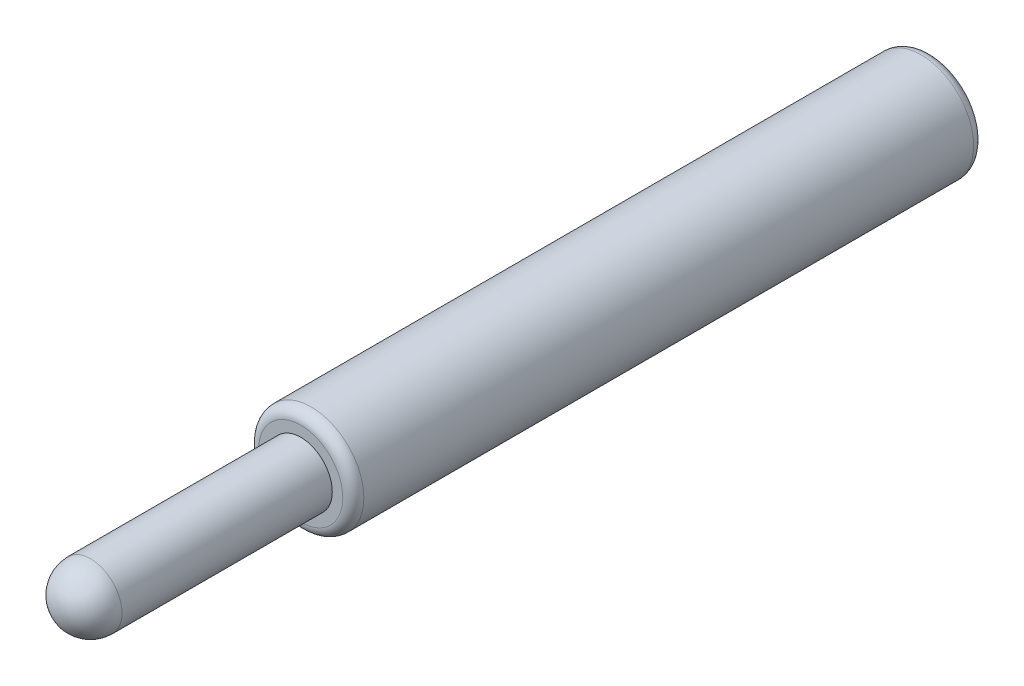
SolidWorks part; units mm, degrees
ref_plane "前视基准面" through (0, 0, 0) normal (0, 0, 1) x (1, 0, 0)
ref_plane "上视基准面" through (0, 0, 0) normal (0, 1, 0) x (1, 0, 0)
ref_plane "右视基准面" through (0, 0, 0) normal (1, 0, 0) x (0, 0, -1)
sketch "草图1" plane through (0, 0, 0) normal (0, 0, 1) x (1, 0, 0)
  circle A0 centre (0, 0) radius 5
  dimension "D1" = 10
extrude "凸台-拉伸1" add sketch "草图1" against normal blind 60
sketch "草图2" plane through (0, 0, 0) normal (0, 0, 1) x (1, 0, 0)
  circle A0 centre (0, 0) radius 3
  dimension "D1" = 6
extrude "凸台-拉伸2" add sketch "草图2" along normal blind 20
fillet "圆角1" radius 1 2 edges at (5, 0, -60) (5, 0, 0)
sketch "草图3" plane through (0, 0, 0) normal (1, 0, 0) x (0, 0, -1)
  line L0 (-20, 0) -> (-20, 3)
  line L1 (-20, 3) -> (-20, -3) construction
  line L2 (-23, 0) -> (-20, 0)
  arc A0 (-20, 3) -> (-23, 0) centre (-20, 0) ccw
  dimension "D1" = 3
revolve "旋转1" add sketch "草图3" angle 360 about L2
ref_plane "基准面4" through (0, 0, 23) normal (0, 0, 1) x (1, 0, 0)
sketch "草图4" plane through (0, 0, 23) normal (0, 0, 1) x (1, 0, 0)
  point P0 (0, 0)
